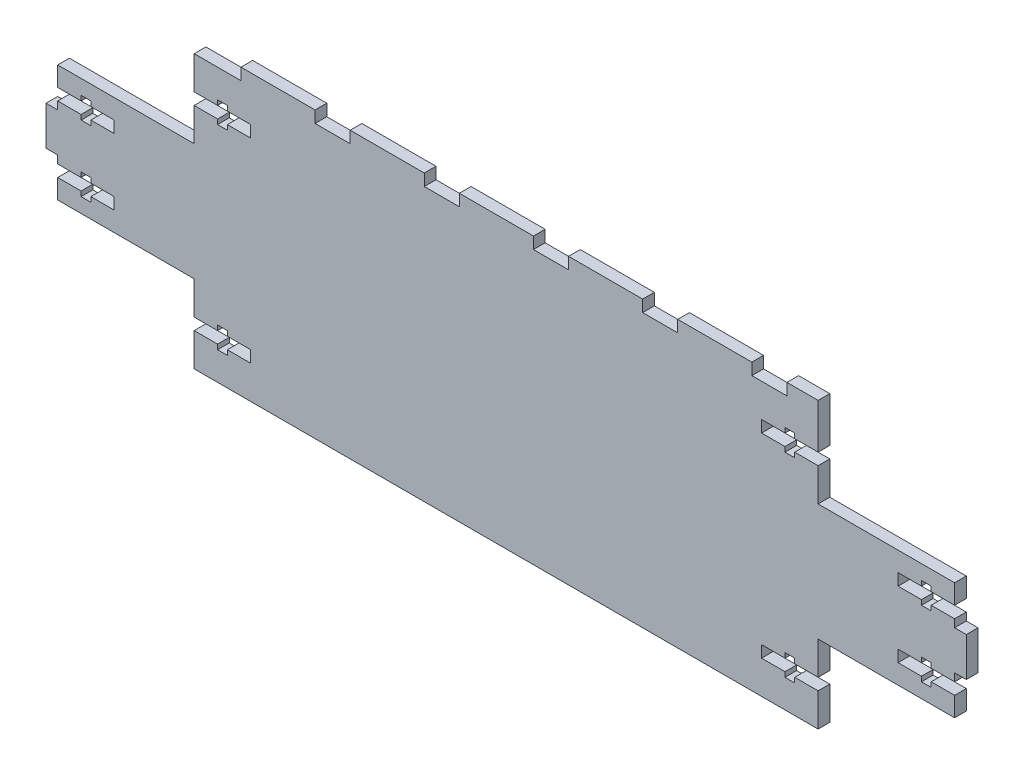
SolidWorks part; units mm, degrees
ref_plane "Спереди" through (0, 0, 0) normal (0, 0, 1) x (1, 0, 0)
ref_plane "Сверху" through (0, 0, 0) normal (0, 1, 0) x (1, 0, 0)
ref_plane "Справа" through (0, 0, 0) normal (1, 0, 0) x (0, 0, -1)
sketch "Эскиз1" plane through (0, 0, 0) normal (0, 0, 1) x (1, 0, 0)
  line L1 (0, 0) -> (160, 0)
  line L2 (0, 0) -> (0, 70)
  line L3 (0, 70) -> (160, 70)
  line L4 (160, 0) -> (160, 70)
  dimension "D1" = 160
  dimension "D2" = 70
extrude "Бобышка-Вытянуть1" add sketch "Эскиз1" along normal blind 3
sketch "Эскиз2" plane through (160, 0, 0) normal (1, 0, 0) x (0, 0, -1)
  line L0 (-3, 0) -> (-3, 70) construction
  line L1 (-3, 20) -> (0, 20)
  line L2 (-3, 20) -> (-3, 50)
  line L3 (-3, 50) -> (0, 50)
  line L4 (0, 20) -> (0, 50)
  line L5 (0, 0) -> (0, 70) construction
  point P8 (-3, 35)
  dimension "D1" = 30
  dimension "D2" = 35
extrude "Бобышка-Вытянуть2" add sketch "Эскиз2" along normal blind 35 and the other way blind 195
sketch "Эскиз3" plane through (195, 0, 0) normal (1, 0, 0) x (0, 0, -1)
  line L0 (-3, 50) -> (-3, 20) construction
  line L1 (-3, 30) -> (0, 30)
  line L2 (-3, 30) -> (-3, 40)
  line L3 (-3, 40) -> (0, 40)
  line L4 (0, 30) -> (0, 40)
  line L5 (0, 20) -> (0, 50) construction
  point P8 (-3, 35)
  dimension "D1" = 10
  dimension "D2" = 35
extrude "Бобышка-Вытянуть3" add sketch "Эскиз3" along normal blind 3 and the other way blind 233
sketch "Эскиз4" plane through (0, 0, 3) normal (0, 0, 1) x (1, 0, 0)
  line L0 (160, 58.5) -> (154, 58.5)
  line L1 (160, 50) -> (160, 70) construction
  line L2 (154, 58.5) -> (154, 57.25)
  line L3 (154, 57.25) -> (151.5, 57.25)
  line L4 (151.5, 57.25) -> (151.5, 58.5)
  line L5 (151.5, 58.5) -> (145.5, 58.5)
  line L6 (145.5, 58.5) -> (145.5, 61.5)
  line L7 (145.5, 61.5) -> (151.5, 61.5)
  line L8 (151.5, 61.5) -> (151.5, 62.75)
  line L9 (151.5, 62.75) -> (154, 62.75)
  line L10 (154, 62.75) -> (154, 61.5)
  line L11 (154, 61.5) -> (160, 61.5)
  line L12 (160, 61.5) -> (160, 58.5)
  line L13 (198, 35) -> (32.5501, 35) construction
  line L14 (198, 40) -> (198, 30) construction
  line L15 (80, 70) -> (80, 16.3204) construction
  line L16 (160, 70) -> (0, 70) construction
  line L17 (160, 8.5) -> (160, 11.5)
  line L18 (154, 8.5) -> (160, 8.5)
  line L19 (154, 7.25) -> (154, 8.5)
  line L20 (151.5, 7.25) -> (154, 7.25)
  line L21 (151.5, 8.5) -> (151.5, 7.25)
  line L22 (145.5, 8.5) -> (151.5, 8.5)
  line L23 (145.5, 11.5) -> (145.5, 8.5)
  line L24 (151.5, 11.5) -> (145.5, 11.5)
  line L25 (151.5, 12.75) -> (151.5, 11.5)
  line L26 (154, 12.75) -> (151.5, 12.75)
  line L27 (154, 11.5) -> (154, 12.75)
  line L28 (160, 11.5) -> (154, 11.5)
  line L29 (0, 11.5) -> (6, 11.5)
  line L30 (6, 11.5) -> (6, 12.75)
  line L31 (6, 12.75) -> (8.5, 12.75)
  line L32 (8.5, 12.75) -> (8.5, 11.5)
  line L33 (8.5, 11.5) -> (14.5, 11.5)
  line L34 (14.5, 11.5) -> (14.5, 8.5)
  line L35 (14.5, 8.5) -> (8.5, 8.5)
  line L36 (8.5, 8.5) -> (8.5, 7.25)
  line L37 (8.5, 7.25) -> (6, 7.25)
  line L38 (6, 7.25) -> (6, 8.5)
  line L39 (6, 8.5) -> (0, 8.5)
  line L40 (0, 8.5) -> (0, 11.5)
  line L41 (0, 61.5) -> (0, 58.5)
  line L42 (6, 61.5) -> (0, 61.5)
  line L43 (6, 62.75) -> (6, 61.5)
  line L44 (8.5, 62.75) -> (6, 62.75)
  line L45 (8.5, 61.5) -> (8.5, 62.75)
  line L46 (14.5, 61.5) -> (8.5, 61.5)
  line L47 (14.5, 58.5) -> (14.5, 61.5)
  line L48 (8.5, 58.5) -> (14.5, 58.5)
  line L49 (8.5, 57.25) -> (8.5, 58.5)
  line L50 (6, 57.25) -> (8.5, 57.25)
  line L51 (6, 58.5) -> (6, 57.25)
  line L52 (0, 58.5) -> (6, 58.5)
  point P10 (160, 60)
  dimension "D1" = 2.5
  dimension "D2" = 5.5
  dimension "D3" = 3
  dimension "D4" = 6
  dimension "D5" = 10
extrude "Вырез-Вытянуть1" cut sketch "Эскиз4" against normal blind 3
sketch "Эскиз5" plane through (0, 0, 3) normal (0, 0, 1) x (1, 0, 0)
  line L0 (195, 45) -> (189, 45)
  line L1 (198, 35) -> (156.9262, 35) construction
  line L2 (195, 50) -> (195, 40) construction
  line L3 (189, 45) -> (189, 46.25)
  line L4 (189, 46.25) -> (186.5, 46.25)
  line L5 (186.5, 46.25) -> (186.5, 45)
  line L6 (186.5, 45) -> (180.5, 45)
  line L7 (180.5, 45) -> (180.5, 42)
  line L8 (180.5, 42) -> (186.5, 42)
  line L9 (186.5, 42) -> (186.5, 40.75)
  line L10 (186.5, 40.75) -> (189, 40.75)
  line L11 (189, 40.75) -> (189, 42)
  line L12 (189, 42) -> (195, 42)
  line L13 (195, 42) -> (195, 45)
  line L14 (198, 40) -> (198, 30) construction
  line L15 (80, 70) -> (80, 12.9981) construction
  line L16 (160, 70) -> (0, 70) construction
  line L17 (195, 28) -> (195, 25)
  line L18 (189, 28) -> (195, 28)
  line L19 (189, 29.25) -> (189, 28)
  line L20 (186.5, 29.25) -> (189, 29.25)
  line L21 (186.5, 28) -> (186.5, 29.25)
  line L22 (180.5, 28) -> (186.5, 28)
  line L23 (180.5, 25) -> (180.5, 28)
  line L24 (186.5, 25) -> (180.5, 25)
  line L25 (186.5, 23.75) -> (186.5, 25)
  line L26 (189, 23.75) -> (186.5, 23.75)
  line L27 (189, 25) -> (189, 23.75)
  line L28 (195, 25) -> (189, 25)
  line L29 (-35, 25) -> (-29, 25)
  line L30 (-29, 25) -> (-29, 23.75)
  line L31 (-29, 23.75) -> (-26.5, 23.75)
  line L32 (-26.5, 23.75) -> (-26.5, 25)
  line L33 (-26.5, 25) -> (-20.5, 25)
  line L34 (-20.5, 25) -> (-20.5, 28)
  line L35 (-20.5, 28) -> (-26.5, 28)
  line L36 (-26.5, 28) -> (-26.5, 29.25)
  line L37 (-26.5, 29.25) -> (-29, 29.25)
  line L38 (-29, 29.25) -> (-29, 28)
  line L39 (-29, 28) -> (-35, 28)
  line L40 (-35, 28) -> (-35, 25)
  line L41 (-35, 42) -> (-35, 45)
  line L42 (-29, 42) -> (-35, 42)
  line L43 (-29, 40.75) -> (-29, 42)
  line L44 (-26.5, 40.75) -> (-29, 40.75)
  line L45 (-26.5, 42) -> (-26.5, 40.75)
  line L46 (-20.5, 42) -> (-26.5, 42)
  line L47 (-20.5, 45) -> (-20.5, 42)
  line L48 (-26.5, 45) -> (-20.5, 45)
  line L49 (-26.5, 46.25) -> (-26.5, 45)
  line L50 (-29, 46.25) -> (-26.5, 46.25)
  line L51 (-29, 45) -> (-29, 46.25)
  line L52 (-35, 45) -> (-29, 45)
  point P59 (195, 43.5)
  dimension "D1" = 2.5
  dimension "D2" = 6
  dimension "D3" = 3
  dimension "D4" = 5.5
  dimension "D5" = 5
  dimension "D6" = 3.5
extrude "Вырез-Вытянуть2" cut sketch "Эскиз5" against normal blind 3
sketch "Эскиз6" plane through (0, 70, 0) normal (0, 1, 0) x (1, 0, 0)
  line L0 (160, 0) -> (0, 0) construction
  line L1 (160, -3) -> (152, -3)
  line L2 (160, -3) -> (160, 0)
  line L3 (160, 0) -> (152, 0)
  line L4 (152, -3) -> (152, 0)
  dimension "D1" = 8
extrude "Бобышка-Вытянуть4" add sketch "Эскиз6" along normal blind 3
sketch "Эскиз7" plane through (0, 70, 0) normal (0, 1, 0) x (1, 0, 0)
  line L0 (152, -3) -> (0, -3) construction
  line L1 (143, -3) -> (124, -3)
  line L2 (143, -3) -> (143, 0)
  line L3 (143, 0) -> (124, 0)
  line L4 (124, -3) -> (124, 0)
  line L5 (152, 0) -> (0, 0) construction
  dimension "D1" = 19
  dimension "D2" = 28
extrude "Бобышка-Вытянуть5" add sketch "Эскиз7" along normal blind 3
pattern_linear "Линейный массив1" count 5 spacing 28 along (-1, 0, 0) of "Бобышка-Вытянуть5"
